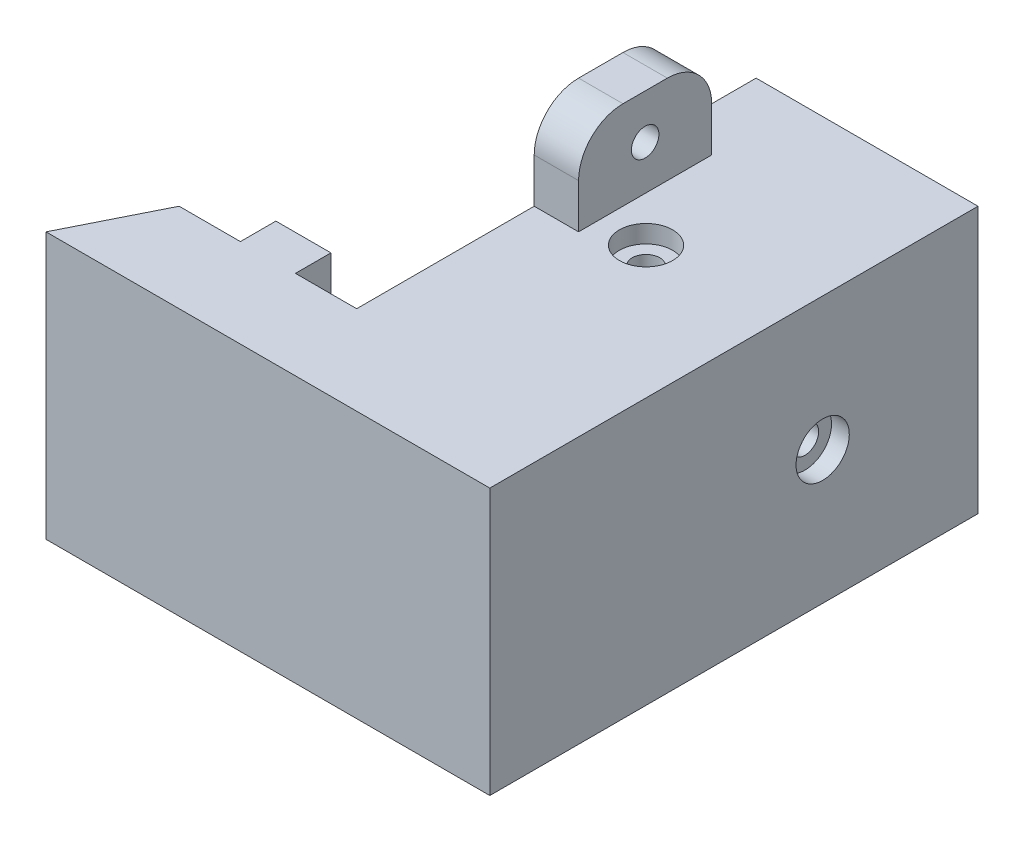
SolidWorks part; units mm, degrees
ref_plane "Front Plane" through (0, 0, 0) normal (0, 0, 1) x (1, 0, 0)
ref_plane "Top Plane" through (0, 0, 0) normal (0, 1, 0) x (1, 0, 0)
ref_plane "Right Plane" through (0, 0, 0) normal (1, 0, 0) x (0, 0, -1)
other "Configuration Table"
sketch "草图1" plane through (0, 0, 0) normal (0, 0, 1) x (1, 0, 0)
  line L0 (-15, 22) -> (-15, -22)
  line L1 (0, 22) -> (15, 22)
  line L2 (0, 22) -> (-15, 22)
  line L3 (15, 22) -> (15, -22)
  line L4 (15, -22) -> (-15, -22)
extrude "凸台-拉伸1" add sketch "草图1" along normal blind 14 contours L0 L4 L3 L1 L2
sketch "草图2" plane through (0, 22, 0) normal (0, 1, 0) x (1, 0, 0)
  line L3 (10, -4) -> (15, -14)
  line L4 (15, -14) -> (-15, -14)
  line L6 (-15, -14) -> (-10, -4)
  line L8 (3.1, -4) -> (3.1, 0)
  line L9 (-15, 0) -> (15, 0) construction
  line L10 (3.1, 0) -> (15, 0)
  line L11 (15, 0) -> (15, -14)
  line L12 (10, -4) -> (3.1, -4)
  line L13 (-3.1, -4) -> (-10, -4)
  line L14 (-15, -14) -> (-15, 0)
  line L15 (-15, 0) -> (-3.1, 0)
  line L16 (-3.1, 0) -> (-3.1, -4)
  line M14 (15, 0) -> (-15, 0)
  line M15 (-15, 0) -> (-15, -14)
  line M17 (15, -14) -> (15, 0)
extrude "切除-拉伸1" cut sketch "草图2" against normal blind 44 contours L16 L6 L13 M14 M15 | L12 L3 L8 M17 M14
sketch "草图8" plane through (0, 0, 4) normal (0, 0, -1) x (-1, 0, 0)
  line L0 (-10, 22) -> (-15, 22)
  line L1 (-15, 22) -> (-15, -22)
  line L2 (-15, -22) -> (-10, -22)
  line L3 (-10, -22) -> (-10, 22)
extrude "切除-拉伸2" cut sketch "草图8" against normal blind 10
sketch "草图9" plane through (0, 0, 4) normal (0, 0, -1) x (-1, 0, 0)
  line L1 (-10, 22) -> (-35, 22)
  line L2 (-10, 22) -> (-10, -22)
  line L3 (-10, -22) -> (-35, -22)
  line L4 (-35, 22) -> (-35, -22)
extrude "凸台-拉伸2" add sketch "草图9" against normal blind 10 contours L2 L1 L4 L3
sketch "草图10" plane through (0, 0, 4) normal (0, 0, -1) x (-1, 0, 0)
  line L0 (15, 22) -> (15, -22) construction
  line L1 (-35, -22) -> (15, -22)
  line L2 (-35, -22) -> (-35, -15)
  line L3 (-35, -15) -> (15, -15)
  line L4 (15, -22) -> (15, -15)
  line L6 (-35, 22) -> (15, 22)
  line L7 (-35, 22) -> (-35, 15)
  line L8 (-35, 15) -> (15, 15)
  line L9 (15, 22) -> (15, 15)
extrude "切除-拉伸3" cut sketch "草图10" against normal blind 10 contours L7 L6 L9 L8 | L2 L1 L4 L3
sketch "草图11" plane through (0, 0, 0) normal (0, 0, -1) x (-1, 0, 0)
  line L0 (3.1, -22) -> (3.1, 22) construction
  line L1 (-3.1, 22) -> (3.1, 22)
  line L2 (-3.1, 22) -> (-3.1, 15)
  line L3 (-3.1, 15) -> (3.1, 15)
  line L4 (3.1, 22) -> (3.1, 15)
  line L5 (-3.1, -22) -> (-3.1, 22) construction
  line L6 (3.1, -22) -> (-3.1, -22)
  line L7 (3.1, -22) -> (3.1, -15)
  line L8 (3.1, -15) -> (-3.1, -15)
  line L9 (-3.1, -22) -> (-3.1, -15)
extrude "切除-拉伸4" cut sketch "草图11" against normal blind 10 contours L7 L6 L9 L8 | L2 L1 L4 L3
sketch "草图12" plane through (0, 0, 4) normal (0, 0, -1) x (-1, 0, 0)
  line L0 (-35, -15) -> (-3.1, -15) construction
  line L1 (-35, 15) -> (-30, 15)
  line L2 (-35, 15) -> (-35, -15)
  line L3 (-35, -15) -> (-30, -15)
  line L4 (-30, 15) -> (-30, -15)
  line L6 (-35, -15) -> (-10, -15)
  line L7 (-35, -15) -> (-35, -10)
  line L8 (-35, -10) -> (-10, -10)
  line L9 (-10, -15) -> (-10, -10)
  line L10 (-35, 15) -> (-10, 15)
  line L11 (-35, 15) -> (-35, 10)
  line L12 (-35, 10) -> (-10, 10)
  line L13 (-10, 15) -> (-10, 10)
  line M13 (-35, -15) -> (-3.1, -15)
extrude "凸台-拉伸3" add sketch "草图12" along normal blind 45 contours L12 L2 L8 L4 | L8 L2 L4 M13 | L9 L8 L4 M13
sketch "草图13" plane through (0, 15, 0) normal (0, 1, 0) x (1, 0, 0)
  line L0 (10, -4) -> (10, 16)
  line L1 (10, 41) -> (10, -4) construction
  line L2 (10, 16) -> (10, 23.5)
  line L3 (10, 23.5) -> (35, 23.5)
  line L4 (35, -14) -> (35, 41) construction
  line L5 (10, 23.5) -> (10, 31)
  line L6 (10, 31) -> (15, 31)
  line L7 (10, 16) -> (15, 16)
  line L8 (15, 16) -> (15, 31)
  line M7 (10, 41) -> (10, -4)
extrude "凸台-拉伸4" add sketch "草图13" along normal blind 10 contours L3 L8 L6 M7 | L7 L8 L3 M7
sketch "草图14" plane through (10, 0, 0) normal (-1, 0, 0) x (0, 0, 1)
  line L0 (-31, 15) -> (-31, -15)
  line L1 (-41, -15) -> (4, -15) construction
  line L2 (-16, 15) -> (-16, -15)
  line L3 (-16, -15) -> (-31, -15)
  line L4 (-31, -15) -> (-31, -25)
  line L5 (-31, -25) -> (-16, -25)
  line L6 (-16, -25) -> (-16, -15)
extrude "凸台-拉伸5" add sketch "草图14" against normal blind 5 contours L5 L6 L3 L4
sketch "草图15" plane through (10, 0, 0) normal (-1, 0, 0) x (0, 0, 1)
  line L0 (-31, 15) -> (-16, 15)
  line L1 (-31, -15) -> (-16, -15)
  line L2 (-41, -15) -> (-31, -15) construction
  line L3 (-31, -15) -> (-31, -25) construction
  line L4 (-23.5, -15) -> (-23.5, 15)
  line L5 (-23.5, 15) -> (-23.5, 20)
  line L6 (-23.5, -15) -> (-23.5, -20)
  circle A0 centre (-23.5, 20) radius 1.55
  circle A1 centre (-23.5, -20) radius 1.55
extrude "切除-拉伸5" cut sketch "草图15" against normal blind 5
sketch "草图16" plane through (10, 0, 0) normal (-1, 0, 0) x (0, 0, 1)
  line L0 (-16, 20) -> (-21, 20)
  line L2 (-31, 20) -> (-31, 25)
  line L3 (-31, 25) -> (-31, 15) construction
  line L4 (-23.5, 20) -> (-23.5, 25)
  line L5 (-31, 25) -> (-16, 25) construction
  line L6 (-31, 15) -> (-16, 15)
  line L7 (-31, 20) -> (-26, 20)
  line L8 (-31, 25) -> (-26, 25)
  line L9 (-16, 25) -> (-16, 15) construction
  line L10 (-21, 25) -> (-16, 25)
  line L11 (-16, 25) -> (-16, 20)
  arc A0 (-31, 20) -> (-26, 25) centre (-26, 20) cw
  arc A1 (-16, 20) -> (-21, 25) centre (-21, 20) ccw
  line M9 (-16, 15) -> (-16, 25)
  line M10 (-16, 25) -> (-31, 25)
  line M11 (-31, 25) -> (-31, 15)
extrude "切除-拉伸6" cut sketch "草图16" against normal blind 5 contours A0 M11 M10 | A1 M9 M10
sketch "草图17" plane through (10, 0, 0) normal (-1, 0, 0) x (0, 0, 1)
  line L0 (-21, -20) -> (-26, -20)
  line L1 (-16, -25) -> (-16, -15) construction
  line L2 (-16, -20) -> (-21, -20)
  line L3 (-31, -25) -> (-16, -25) construction
  line L4 (-31, -15) -> (-31, -25) construction
  line L5 (-31, -20) -> (-31, -25)
  line L6 (-31, -25) -> (-26, -25)
  line L7 (-16, -20) -> (-16, -25)
  line L8 (-16, -25) -> (-21, -25)
  arc A0 (-16, -20) -> (-21, -25) centre (-21, -20) cw
  arc A1 (-31, -20) -> (-26, -25) centre (-26, -20) ccw
  line M11 (-31, -15) -> (-31, -25)
  line M12 (-31, -25) -> (-16, -25)
  line M13 (-16, -25) -> (-16, -15)
extrude "切除-拉伸7" cut sketch "草图17" against normal blind 5 contours A1 M11 M12 | A0 M13 M12
sketch "草图18" plane through (0, -15, 0) normal (0, -1, 0) x (1, 0, 0)
  line L0 (10, -41) -> (10, -31)
  line L1 (10, -31) -> (0, -31)
  line L2 (0, -41) -> (10, -41)
  arc A0 (10, -31) -> (0, -41) centre (0, -31) cw
extrude "凸台-拉伸6" add sketch "草图18" against normal blind 5 contours A0 L2 L0
sketch "草图19" plane through (0, 15, 0) normal (0, 1, 0) x (1, 0, 0)
  line L0 (10, 41) -> (0, 41)
  line L1 (0, 41) -> (10, 41)
  line L2 (10, 31) -> (10, 41)
  arc A0 (10, 31) -> (0, 41) centre (0, 31) ccw
extrude "凸台-拉伸7" add sketch "草图19" against normal blind 5 contours A0 L2 L0
sketch "草图20" plane through (0, 0, -41) normal (0, 0, -1) x (-1, 0, 0)
  line L1 (-30, 10) -> (-30.2, 10)
  line L2 (-30, 10) -> (-30, -10)
  line L3 (-30, -10) -> (-30.2, -10)
  line L4 (-30.2, 10) -> (-30.2, -10)
extrude "切除-拉伸8" cut sketch "草图20" against normal blind 45
sketch "草图21" plane through (0, 15, 0) normal (0, 1, 0) x (1, 0, 0)
  line L0 (0, 41) -> (10, 41)
  line L1 (35, 41) -> (0, 41) construction
  line L2 (10, 41) -> (10, 31)
  line L3 (10, 31) -> (0, 31)
  arc A0 (10, 31) -> (0, 41) centre (0, 31) ccw
  arc A1 (10, 31) -> (0, 41) centre (0, 31) ccw construction
  line M2 (35, 41) -> (0, 41)
  arc M3 (0, 41) -> (10, 31) centre (0, 31) cw
extrude "切除-拉伸9" cut sketch "草图21" against normal blind 100 contours L2 M2 M3
sketch "草图23" plane through (0, 10, 0) normal (0, -1, 0) x (1, 0, 0)
  line L0 (30.2, 4) -> (10, -41)
  circle A0 centre (20.1, -18.5) radius 1.55
extrude "切除-拉伸10" cut sketch "草图23" against normal blind 100 contours L0 A0 | L0 A0
sketch "草图24" plane through (0, 15, 0) normal (0, 1, 0) x (1, 0, 0)
  circle A0 centre (20.1, 18.5) radius 1.55
extrude "切除-拉伸11" cut sketch "草图24" against normal blind 100 contours A0
sketch "草图25" plane through (0, -15, 0) normal (0, -1, 0) x (1, 0, 0)
  circle A0 centre (20.1, -18.5) radius 3
  circle M2 centre (20.1, -18.5) radius 1.55
extrude "切除-拉伸12" cut sketch "草图25" against normal blind 2 contours A0 M2
sketch "草图26" plane through (0, 15, 0) normal (0, 1, 0) x (1, 0, 0)
  circle A0 centre (20.1, 18.5) radius 3
extrude "切除-拉伸13" cut sketch "草图26" against normal blind 2
sketch "草图27" plane through (35, 0, 0) normal (1, 0, 0) x (0, 0, -1)
  line L0 (23.5, 20) -> (23.5, -20)
  line L1 (23.5, 0) -> (41, 0)
  line L2 (41, 15) -> (41, -15) construction
  circle A0 centre (23.5, 0) radius 1.55
extrude "切除-拉伸14" cut sketch "草图27" against normal blind 5 contours L1 A0 L0 | L0 A0 | L0 A0 L1
sketch "草图28" plane through (35, 0, 0) normal (1, 0, 0) x (0, 0, -1)
  circle A0 centre (23.5, 0) radius 3
extrude "切除-拉伸15" cut sketch "草图28" against normal blind 2
